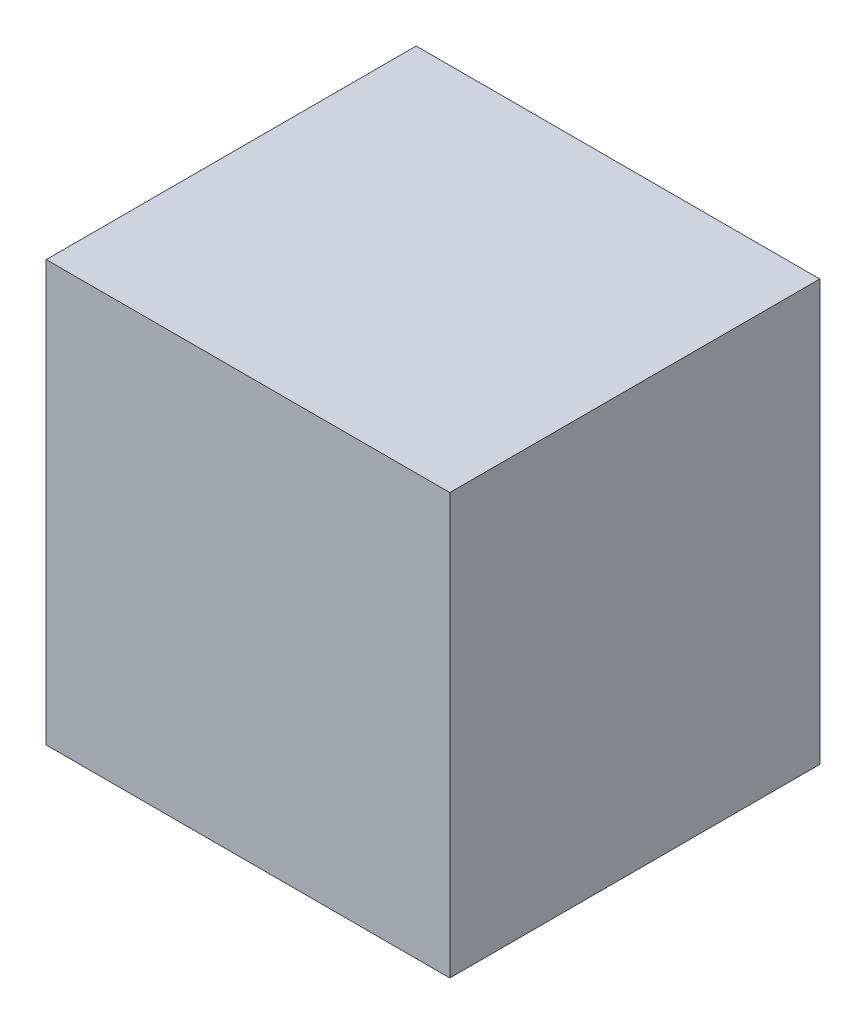
SolidWorks part; units mm, degrees
ref_plane "Front Plane" through (0, 0, 0) normal (0, 0, 1) x (1, 0, 0)
ref_plane "Top Plane" through (0, 0, 0) normal (0, 1, 0) x (1, 0, 0)
ref_plane "Right Plane" through (0, 0, 0) normal (1, 0, 0) x (0, 0, -1)
sketch "Sketch1" plane through (0, 0, 0) normal (0, 1, 0) x (1, 0, 0)
  line L1 (0, 0) -> (76.2, 0)
  line L2 (0, 0) -> (0, 69.85)
  line L3 (0, 69.85) -> (76.2, 69.85)
  line L4 (76.2, 0) -> (76.2, 69.85)
  dimension "D1" = 69.85
  dimension "D2" = 76.2
extrude "Boss-Extrude1" add sketch "Sketch1" along normal blind 79.375
